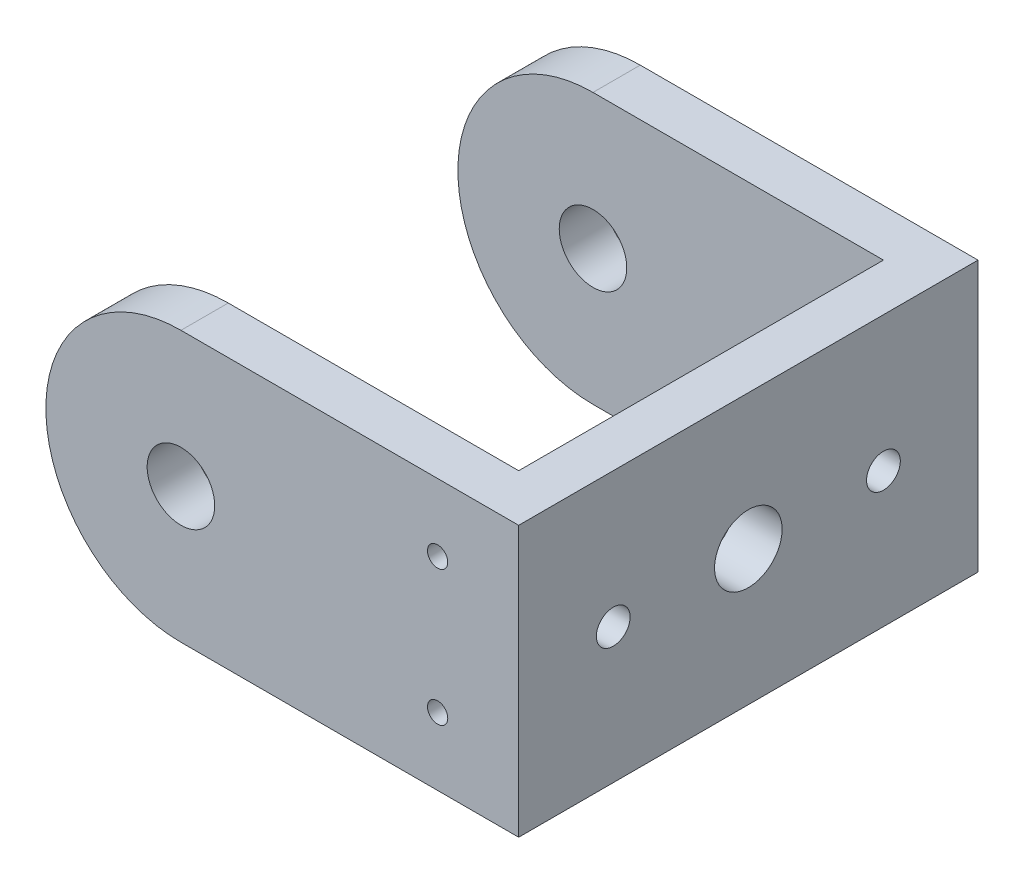
SolidWorks part; units mm, degrees
ref_plane "正面" through (0, 0, 0) normal (0, 0, 1) x (1, 0, 0)
ref_plane "平面" through (0, 0, 0) normal (0, 1, 0) x (1, 0, 0)
ref_plane "右側面" through (0, 0, 0) normal (1, 0, 0) x (0, 0, -1)
sketch "ｽｹｯﾁ1" plane through (0, 0, 0) normal (0, 0, 1) x (1, 0, 0)
  line L0 (0, 0) -> (0, -40)
  line L1 (0, -40) -> (-50, -40)
  line L2 (-50, 0) -> (0, 0)
  arc A0 (-50, -40) -> (-50, 0) centre (-50, -20) cw
  circle A1 centre (-50, -20) radius 5
  dimension "D3" = 10
  dimension "D1" = 50
  dimension "D2" = 40
extrude "ﾎﾞｽ - 押し出し1" add sketch "ｽｹｯﾁ1" along normal blind 68
sketch "ｽｹｯﾁ2" plane through (0, 0, 0) normal (0, 1, 0) x (1, 0, 0)
  line L0 (0, -34) -> (-87.3418, -34) construction
  line L1 (-75.7688, -7) -> (-7, -7)
  line L2 (-75.7688, -7) -> (-75.7688, -61)
  line L3 (-75.7688, -61) -> (-7, -61)
  line L4 (-7, -7) -> (-7, -61)
  line L5 (0, -68) -> (0, 0) construction
  line L6 (0, 0) -> (-50, 0) construction
  dimension "D1" = 7
  dimension "D2" = 7
extrude "ｶｯﾄ - 押し出し1" cut sketch "ｽｹｯﾁ2" against normal through all
sketch "ｽｹｯﾁ3" plane through (0, 0, 0) normal (1, 0, 0) x (0, 0, -1)
  line L0 (-68, -20) -> (0, -20) construction
  line L1 (-68, -40) -> (-68, 0) construction
  line L2 (0, -40) -> (0, 0) construction
  line L3 (-34, -20) -> (-34, -40) construction
  line L4 (-68, -40) -> (0, -40) construction
  circle A0 centre (-34, -20) radius 5
  circle A1 centre (-54, -20) radius 2.5
  circle A2 centre (-14, -20) radius 2.5
  dimension "D1" = 10
  dimension "D2" = 5
  dimension "D3" = 40
extrude "ｶｯﾄ - 押し出し2" cut sketch "ｽｹｯﾁ3" against normal through all
sketch "ｽｹｯﾁ4" plane through (0, 0, 0) normal (0, 0, -1) x (-1, 0, 0)
  line L0 (0, -20) -> (45, -20) construction
  line L1 (0, -40) -> (0, 0) construction
  circle A0 centre (50, -20) radius 5 construction
  circle A1 centre (12, -10) radius 1.5
  circle A2 centre (12, -30) radius 1.5
  dimension "D1" = 3
  dimension "D2" = 20
  dimension "D3" = 12
extrude "ｶｯﾄ - 押し出し3" cut sketch "ｽｹｯﾁ4" against normal through all
